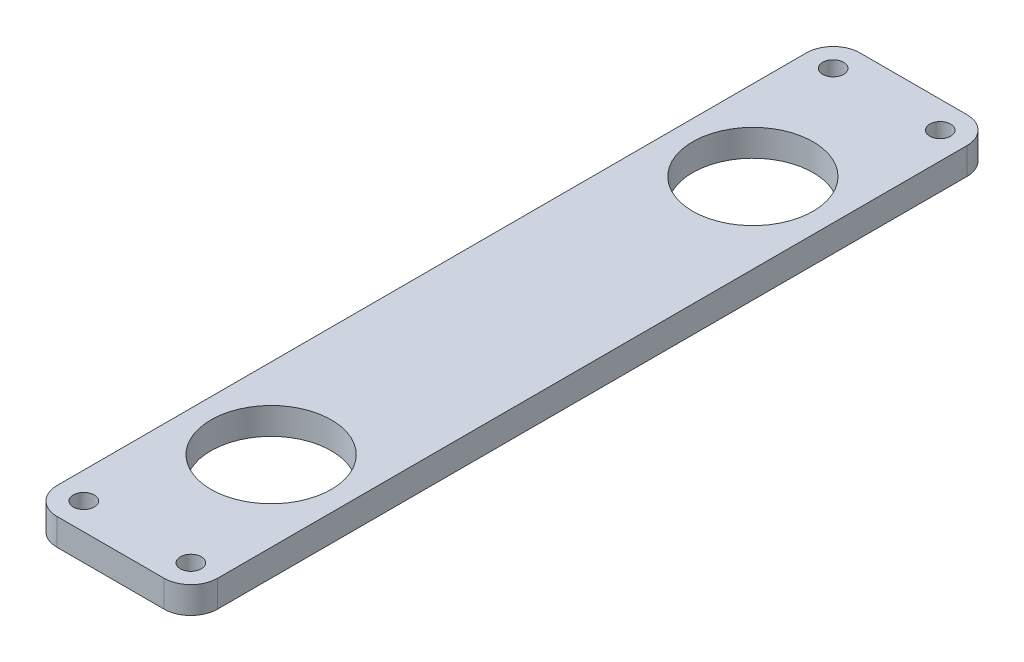
SolidWorks part; units mm, degrees
material "PC High Viscosity"
ref_plane "Front Plane" through (0, 0, 0) normal (0, 0, 1) x (1, 0, 0)
ref_plane "Top Plane" through (0, 0, 0) normal (0, 1, 0) x (1, 0, 0)
ref_plane "Right Plane" through (0, 0, 0) normal (1, 0, 0) x (0, 0, -1)
sketch "Sketch1" plane through (0, 0, 0) normal (0, 1, 0) x (1, 0, 0)
  line L1 (-19.05, -38.1) -> (19.05, -38.1)
  line L2 (-19.05, -38.1) -> (-19.05, 152.4)
  line L3 (-19.05, 152.4) -> (19.05, 152.4)
  line L4 (19.05, -38.1) -> (19.05, 152.4)
  circle A0 centre (0, 0) radius 14.2875
  circle A1 centre (0, 114.3) radius 14.2875
  circle A4 centre (-12.7, 146.05) radius 2.4892
  circle A5 centre (12.7, 146.05) radius 2.4892
  circle A6 centre (-12.7, -31.75) radius 2.4892
  circle A7 centre (12.7, -31.75) radius 2.4892
  point P17 (0, 0)
  point P18 (0, 0)
  point P19 (0, 0)
  point P20 (0, 0)
  dimension "D1" = 28.575
  dimension "D2" = 114.3
  dimension "D3" = 38.1
  dimension "D6" = 38.1
  dimension "D7" = 4.9784
  dimension "D8" = 6.35
  dimension "D9" = 25.4
  dimension "D10" = 6.35
  dimension "D11" = 6.35
  dimension "D4" = 19.05
  dimension "D5" = 38.1
extrude "Boss-Extrude1" add sketch "Sketch1" along normal mid plane 6.35
fillet "Fillet1" radius 6.35 4 edges at (-19.05, 0, -152.4) (19.05, 0, -152.4) (-19.05, 0, 38.1) (19.05, 0, 38.1)
